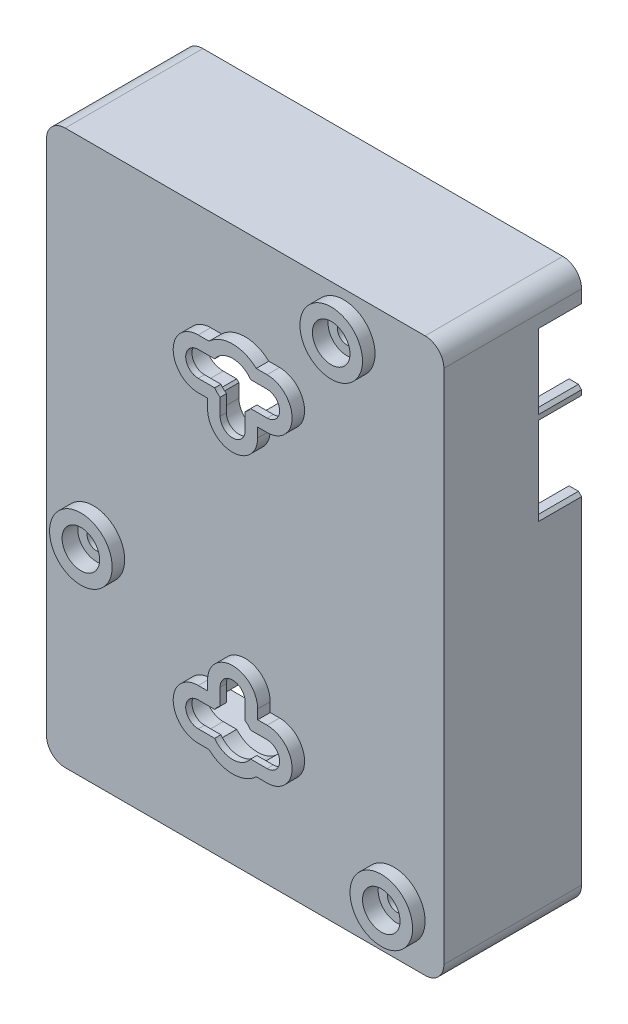
SolidWorks part; units mm, degrees
ref_plane "Front Plane" through (0, 0, 0) normal (0, 0, 1) x (1, 0, 0)
ref_plane "Top Plane" through (0, 0, 0) normal (0, 1, 0) x (1, 0, 0)
ref_plane "Right Plane" through (0, 0, 0) normal (1, 0, 0) x (0, 0, -1)
ref_plane "Plane1" through (0, 0, 2) normal (0, 0, 1) x (1, 0, 0)
sketch "Sketch2" plane through (0, 0, 2) normal (0, 0, 1) x (1, 0, 0)
  line L0 (-36.8212, -25.2032) -> (-36.8212, 57.2968) construction
  line L1 (-39.8212, 60.2968) -> (23.6788, 60.2968)
  line L2 (-39.8212, 60.2968) -> (-39.8212, -28.2032)
  line L3 (-39.8212, -28.2032) -> (23.6788, -28.2032)
  line L4 (23.6788, 60.2968) -> (23.6788, -28.2032)
  line L5 (-36.8212, 57.2968) -> (20.6788, 57.2968) construction
  line L6 (20.6788, 57.2968) -> (20.6788, -25.2032) construction
  line L7 (20.6788, -25.2032) -> (-36.8212, -25.2032) construction
  dimension "D1" = 3
  dimension "D2" = 3
  dimension "D3" = 3
  dimension "D4" = 3
extrude "Boss-Extrude1" add sketch "Sketch2" along normal blind 2
sketch "Sketch3" plane through (0, 0, 2) normal (0, 0, -1) x (-1, 0, 0)
  line L4 (39.8212, -28.2032) -> (39.8212, 60.2968)
  line L5 (39.8212, 60.2968) -> (-23.6788, 60.2968)
  line L6 (-23.6788, 60.2968) -> (-23.6788, -28.2032)
  line L7 (-23.6788, -28.2032) -> (39.8212, -28.2032)
  line L8 (39.8212, -28.2032) -> (39.8212, 60.2968)
  line L9 (39.8212, 60.2968) -> (-23.6788, 60.2968)
  line L10 (-23.6788, 60.2968) -> (-23.6788, -28.2032)
  line L11 (-23.6788, -28.2032) -> (39.8212, -28.2032)
  line L16 (37.8212, -26.2032) -> (37.8212, 58.2968)
  line L17 (37.8212, 58.2968) -> (-21.6788, 58.2968)
  line L18 (-21.6788, 58.2968) -> (-21.6788, -26.2032)
  line L19 (-21.6788, -26.2032) -> (37.8212, -26.2032)
  line L20 (37.8212, -26.2032) -> (37.8212, 58.2968)
  line L21 (37.8212, 58.2968) -> (-21.6788, 58.2968)
  line L22 (-21.6788, 58.2968) -> (-21.6788, -26.2032)
  line L23 (-21.6788, -26.2032) -> (37.8212, -26.2032)
  dimension "D1" = 0
  dimension "D2" = 2
extrude "Boss-Extrude2" add sketch "Sketch3" along normal blind 20
sketch "Sketch4" plane through (23.6788, 0, 0) normal (1, 0, 0) x (0, 0, -1)
  line L0 (18, 60.2968) -> (18, -28.2032) construction
  line L1 (18, 29.0468) -> (11.65, 29.0468)
  line L2 (18, 29.0468) -> (18, 42.0468)
  line L3 (18, 42.0468) -> (11.65, 42.0468)
  line L4 (11.65, 29.0468) -> (11.65, 42.0468)
  line L5 (11.65, -25.2032) -> (11.65, 57.2968) construction
  line L7 (18, 43.8468) -> (11.65, 43.8468)
  line L8 (18, 43.8468) -> (18, 54.7468)
  line L9 (18, 54.7468) -> (11.65, 54.7468)
  line L10 (11.65, 43.8468) -> (11.65, 54.7468)
  line L11 (16.95, 47.7968) -> (16.95, 50.7968) construction
  line L12 (16.95, 32.7968) -> (16.95, 38.2968) construction
  point P16 (16.95, 49.2968)
  point P17 (11.65, 49.2968)
  point P18 (16.95, 35.5468)
  point P19 (11.65, 35.5468)
  dimension "D1" = 10.9
  dimension "D2" = 13
extrude "Cut-Extrude1" cut sketch "Sketch4" against normal up to surface (2 mm away) up to face at (21.6788, 16.0468, -8)
chamfer "Chamfer1" distance 0.5 angle 45 6 edges at (23.6788, 54.7468, -14.825) (23.6788, 49.2968, -11.65) (23.6788, 43.8468, -14.825) (23.6788, 42.0468, -14.825) (23.6788, 35.5468, -11.65) (23.6788, 29.0468, -14.825)
sketch "Sketch5" plane through (-39.8212, 0, 0) normal (-1, 0, 0) x (0, 0, 1)
  line L0 (-18, -28.2032) -> (-18, 60.2968) construction
  line L1 (4, 60.2968) -> (-18, 60.2968) construction
  line L2 (-11.65, 57.2968) -> (-11.65, -25.2032) construction
  line L3 (-18, 34.207) -> (-11.65, 34.207)
  line L4 (-18, 34.207) -> (-18, 9.207)
  line L5 (-18, 9.207) -> (-11.65, 9.207)
  line L6 (-11.65, 34.207) -> (-11.65, 9.207)
  circle A0 centre (-12.432, 40.6543) radius 0.75
  point P12 (-11.65, 33.6258)
  point P13 (-18, 7.3997)
  point P14 (-18, 3.9836)
  point P15 (-18, 9.207)
  dimension "D1" = 1.5
  dimension "D2" = 5.568
  dimension "D3" = 19.6425
  dimension "D4" = 25
extrude "Cut-Extrude3" cut sketch "Sketch5" against normal up to surface (2 mm away) up to face at (-37.8212, 16.0468, -8)
fillet "Fillet1" radius 6 2 edges at (-38.8212, 9.207, -18) (-38.8212, 34.207, -18)
sketch "Sketch6" plane through (0, -28.2032, 0) normal (0, -1, 0) x (1, 0, 0)
  line L0 (23.6788, -18) -> (-39.8212, -18) construction
  line L1 (13.0098, -18) -> (-13.7903, -18)
  line L2 (13.0098, -18) -> (13.0098, -11.65)
  line L3 (13.0098, -11.65) -> (-13.7903, -11.65)
  line L4 (-13.7903, -18) -> (-13.7903, -11.65)
  line L5 (-36.8212, -11.65) -> (20.6788, -11.65) construction
  point P8 (-13.7903, -18)
extrude "Cut-Extrude4" cut sketch "Sketch6" against normal up to surface (2 mm away) up to face at (-8.0712, -26.2032, -8)
fillet "Fillet2" radius 3 4 edges at (-39.8212, 60.2968, -7) (23.6788, 60.2968, -7) (23.6788, -28.2032, -7) (-39.8212, -28.2032, -7)
sketch "Sketch7" plane through (0, 0, 4) normal (0, 0, 1) x (1, 0, 0)
  line L0 (-8.0712, -28.2032) -> (-8.0712, 60.2968) construction
  line L1 (-36.8212, -28.2032) -> (20.6788, -28.2032) construction
  line L2 (20.6788, 60.2968) -> (-36.8212, 60.2968) construction
  line L3 (-2.5712, -8.2032) -> (-13.5712, -8.2032) construction
  line L4 (-2.5712, -10.2032) -> (-5.199, -10.2032)
  line L5 (-2.5712, -6.2032) -> (-5.199, -6.2032)
  line L6 (23.6788, 16.0468) -> (-39.8212, 16.0468) construction
  line L7 (23.6788, -25.2032) -> (23.6788, 57.2968) construction
  line L8 (-39.8212, 57.2968) -> (-39.8212, -25.2032) construction
  line L9 (-10.0712, -2.7032) -> (-10.0712, -5.3309)
  line L10 (-6.0712, -2.7032) -> (-6.0712, -5.3309)
  line L11 (-10.9435, -6.2032) -> (-13.5712, -6.2032)
  line L12 (-10.9435, -10.2032) -> (-13.5712, -10.2032)
  line L13 (-6.0712, 34.7968) -> (-6.0712, 37.4245)
  line L14 (-2.5712, 38.2968) -> (-5.199, 38.2968)
  line L15 (-2.5712, 42.2968) -> (-5.199, 42.2968)
  line L16 (-10.9435, 42.2968) -> (-13.5712, 42.2968)
  line L17 (-10.9435, 38.2968) -> (-13.5712, 38.2968)
  line L18 (-10.0712, 34.7968) -> (-10.0712, 37.4245)
  arc A0 (-2.5712, -10.2032) -> (-2.5712, -6.2032) centre (-2.5712, -8.2032) ccw
  arc A1 (-13.5712, -6.2032) -> (-13.5712, -10.2032) centre (-13.5712, -8.2032) ccw
  arc A2 (-6.0712, -2.7032) -> (-10.0712, -2.7032) centre (-8.0712, -2.7032) ccw
  arc A3 (-10.0712, -5.3309) -> (-10.9435, -6.2032) centre (-8.0712, -8.2032) ccw
  arc A4 (-5.199, -6.2032) -> (-6.0712, -5.3309) centre (-8.0712, -8.2032) ccw
  arc A5 (-10.9435, -10.2032) -> (-5.199, -10.2032) centre (-8.0712, -8.2032) ccw
  arc A6 (-6.0712, 34.7968) -> (-10.0712, 34.7968) centre (-8.0712, 34.7968) cw
  arc A7 (-5.199, 38.2968) -> (-6.0712, 37.4245) centre (-8.0712, 40.2968) cw
  arc A8 (-2.5712, 42.2968) -> (-2.5712, 38.2968) centre (-2.5712, 40.2968) cw
  arc A9 (-10.9435, 42.2968) -> (-5.199, 42.2968) centre (-8.0712, 40.2968) cw
  arc A10 (-13.5712, 38.2968) -> (-13.5712, 42.2968) centre (-13.5712, 40.2968) cw
  arc A11 (-10.0712, 37.4245) -> (-10.9435, 38.2968) centre (-8.0712, 40.2968) cw
  point P8 (-8.0712, -8.2032)
  dimension "D4" = 4
  dimension "D6" = 7
  dimension "D1" = 11
  dimension "D2" = 4
  dimension "D3" = 20
  dimension "D5" = 5.5
extrude "Cut-Extrude5" cut sketch "Sketch7" against normal blind 10
sketch "Sketch8" plane through (0, 0, 4) normal (0, 0, 1) x (1, 0, 0)
  line L0 (-2.5712, 42.2968) -> (-5.199, 42.2968) construction
  line L1 (-5.199, 38.2968) -> (-2.5712, 38.2968) construction
  line L2 (-6.0712, 34.7968) -> (-6.0712, 37.4245) construction
  line L3 (-10.0712, 37.4245) -> (-10.0712, 34.7968) construction
  line L4 (-13.5712, 38.2968) -> (-10.9435, 38.2968) construction
  line L5 (-10.9435, 42.2968) -> (-13.5712, 42.2968) construction
  line L6 (-2.5712, 42.2968) -> (-5.199, 42.2968)
  line L7 (-5.199, 38.2968) -> (-2.5712, 38.2968)
  line L8 (-6.0712, 34.7968) -> (-6.0712, 37.4245)
  line L9 (-10.0712, 37.4245) -> (-10.0712, 34.7968)
  line L10 (-13.5712, 38.2968) -> (-10.9435, 38.2968)
  line L11 (-10.9435, 42.2968) -> (-13.5712, 42.2968)
  line L12 (-11.8462, 44.2968) -> (-13.5712, 44.2968)
  line L13 (-13.5712, 36.2968) -> (-12.0712, 36.2968)
  line L14 (-12.0712, 36.2968) -> (-12.0712, 34.7968)
  line L15 (-4.0712, 34.7968) -> (-4.0712, 36.2968)
  line L16 (-4.0712, 36.2968) -> (-2.5712, 36.2968)
  line L17 (-2.5712, 44.2968) -> (-4.2963, 44.2968)
  arc A0 (-2.5712, 38.2968) -> (-2.5712, 42.2968) centre (-2.5712, 40.2968) ccw construction
  arc A1 (-6.0712, 37.4245) -> (-5.199, 38.2968) centre (-8.0712, 40.2968) ccw construction
  arc A2 (-10.0712, 34.7968) -> (-6.0712, 34.7968) centre (-8.0712, 34.7968) ccw construction
  arc A3 (-10.9435, 38.2968) -> (-10.0712, 37.4245) centre (-8.0712, 40.2968) ccw construction
  arc A4 (-13.5712, 42.2968) -> (-13.5712, 38.2968) centre (-13.5712, 40.2968) ccw construction
  arc A5 (-5.199, 42.2968) -> (-10.9435, 42.2968) centre (-8.0712, 40.2968) ccw construction
  arc A6 (-2.5712, 38.2968) -> (-2.5712, 42.2968) centre (-2.5712, 40.2968) ccw
  arc A7 (-6.0712, 37.4245) -> (-5.199, 38.2968) centre (-8.0712, 40.2968) ccw
  arc A8 (-10.0712, 34.7968) -> (-6.0712, 34.7968) centre (-8.0712, 34.7968) ccw
  arc A9 (-10.9435, 38.2968) -> (-10.0712, 37.4245) centre (-8.0712, 40.2968) ccw
  arc A10 (-13.5712, 42.2968) -> (-13.5712, 38.2968) centre (-13.5712, 40.2968) ccw
  arc A11 (-5.199, 42.2968) -> (-10.9435, 42.2968) centre (-8.0712, 40.2968) ccw
  arc A12 (-4.2963, 44.2968) -> (-11.8462, 44.2968) centre (-8.0712, 40.2968) ccw
  arc A13 (-13.5712, 44.2968) -> (-13.5712, 36.2968) centre (-13.5712, 40.2968) ccw
  arc A14 (-12.0712, 36.2968) -> (-12.0712, 36.2968) centre (-12.0712, 36.2968) cw
  arc A15 (-12.0712, 34.7968) -> (-4.0712, 34.7968) centre (-8.0712, 34.7968) ccw
  arc A16 (-4.0712, 36.2968) -> (-4.0712, 36.2968) centre (-4.0712, 36.2968) cw
  arc A17 (-2.5712, 36.2968) -> (-2.5712, 44.2968) centre (-2.5712, 40.2968) ccw
  dimension "D1" = 2
extrude "Boss-Extrude3" add sketch "Sketch8" along normal blind 2
sketch "Sketch9" plane through (0, 0, 2) normal (0, 0, -1) x (-1, 0, 0)
  circle A0 centre (-15.6788, -20.7032) radius 3.5
  circle A1 centre (32.3212, 5.2968) radius 3.5
  circle A2 centre (-7.6788, 53.7968) radius 2.5
  dimension "D1" = 7
  dimension "D2" = 7
  dimension "D3" = 5
extrude "Boss-Extrude4" add sketch "Sketch9" along normal up to surface (12.05 mm away)
sketch "Sketch10" plane through (0, 0, 4) normal (0, 0, 1) x (1, 0, 0)
  circle A0 centre (7.6788, 53.7968) radius 1.5
  circle A1 centre (15.6788, -20.7032) radius 1.5
  circle A2 centre (-32.3212, 5.2968) radius 1.5
  dimension "D1" = 3
extrude "Cut-Extrude6" cut sketch "Sketch10" against normal through all
sketch "Sketch11" plane through (0, 0, 4) normal (0, 0, 1) x (1, 0, 0)
  circle A0 centre (7.6788, 53.7968) radius 3
  circle A2 centre (-32.3212, 5.2968) radius 3
  circle A3 centre (15.6788, -20.7032) radius 3
  dimension "D1" = 6
extrude "Cut-Extrude7" cut sketch "Sketch11" against normal blind 0.5
sketch "Sketch12" plane through (0, 0, 4) normal (0, 0, 1) x (1, 0, 0)
  circle A0 centre (15.6788, -20.7032) radius 3 construction
  circle A1 centre (-32.3212, 5.2968) radius 3 construction
  circle A2 centre (7.6788, 53.7968) radius 3 construction
  circle A3 centre (15.6788, -20.7032) radius 3
  circle A4 centre (-32.3212, 5.2968) radius 3
  circle A5 centre (7.6788, 53.7968) radius 3
  circle A6 centre (7.6788, 53.7968) radius 5
  circle A7 centre (-32.3212, 5.2968) radius 5
  circle A8 centre (15.6788, -20.7032) radius 5
  dimension "D1" = 2
extrude "Boss-Extrude5" add sketch "Sketch12" along normal blind 2
sketch "Sketch13" plane through (0, 0, 2) normal (0, 0, -1) x (-1, 0, 0)
  line L44 (13.5712, 43.2968) -> (11.4253, 43.2968)
  line L45 (11.4253, 37.2968) -> (13.5712, 37.2968)
  line L46 (11.0712, 34.7968) -> (11.0712, 36.9427)
  line L47 (5.0712, 36.9427) -> (5.0712, 34.7968)
  line L48 (2.5712, 37.2968) -> (4.7171, 37.2968)
  line L49 (4.7171, 43.2968) -> (2.5712, 43.2968)
  line L50 (13.5712, 43.2968) -> (11.4253, 43.2968)
  line L51 (11.4253, 37.2968) -> (13.5712, 37.2968)
  line L52 (11.0712, 34.7968) -> (11.0712, 36.9427)
  line L53 (5.0712, 36.9427) -> (5.0712, 34.7968)
  line L54 (2.5712, 37.2968) -> (4.7171, 37.2968)
  line L55 (4.7171, 43.2968) -> (2.5712, 43.2968)
  arc A50 (13.5712, 37.2968) -> (13.5712, 43.2968) centre (13.5712, 40.2968) ccw
  arc A51 (11.0712, 36.9427) -> (11.4253, 37.2968) centre (8.0712, 40.2968) ccw
  arc A52 (5.0712, 34.7968) -> (11.0712, 34.7968) centre (8.0712, 34.7968) ccw
  arc A53 (4.7171, 37.2968) -> (5.0712, 36.9427) centre (8.0712, 40.2968) ccw
  arc A54 (2.5712, 43.2968) -> (2.5712, 37.2968) centre (2.5712, 40.2968) ccw
  arc A55 (11.4253, 43.2968) -> (4.7171, 43.2968) centre (8.0712, 40.2968) ccw
  arc A56 (13.5712, 37.2968) -> (13.5712, 43.2968) centre (13.5712, 40.2968) ccw
  arc A57 (11.0712, 36.9427) -> (11.4253, 37.2968) centre (8.0712, 40.2968) ccw
  arc A58 (5.0712, 34.7968) -> (11.0712, 34.7968) centre (8.0712, 34.7968) ccw
  arc A59 (4.7171, 37.2968) -> (5.0712, 36.9427) centre (8.0712, 40.2968) ccw
  arc A60 (2.5712, 43.2968) -> (2.5712, 37.2968) centre (2.5712, 40.2968) ccw
  arc A61 (11.4253, 43.2968) -> (4.7171, 43.2968) centre (8.0712, 40.2968) ccw
  dimension "D1" = 1
extrude "Cut-Extrude8" cut sketch "Sketch13" against normal blind 3
ref_plane "Plane2" through (0, 16.0468, 0) normal (0, 1, 0) x (1, 0, 0)
mirror "Mirror1" about plane through (0, 16.0468, 0) normal (0, 1, 0) of "Cut-Extrude8", "Boss-Extrude3"
